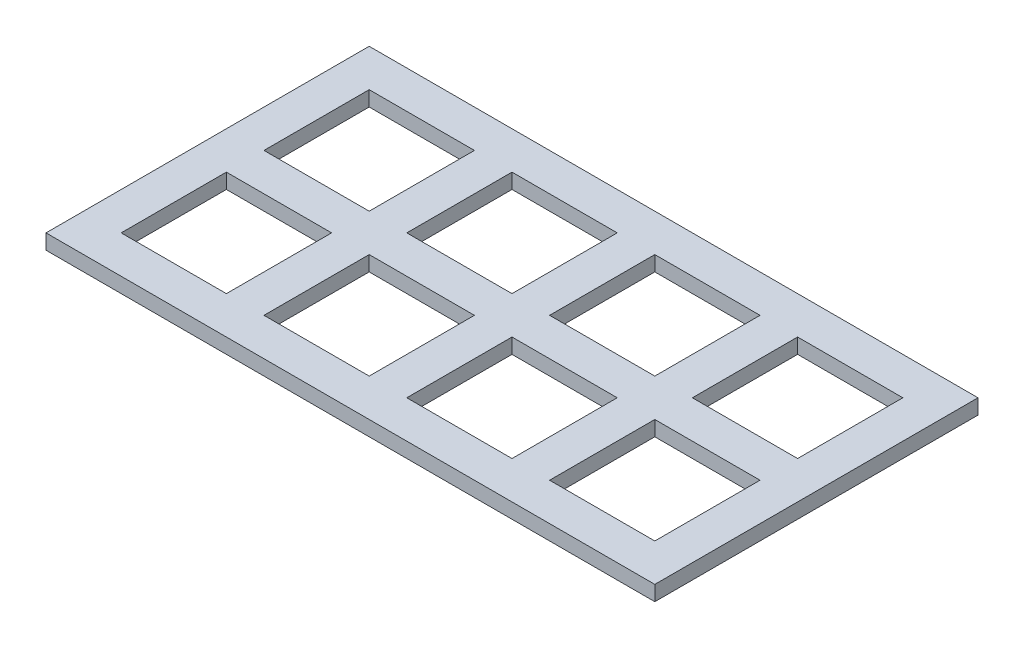
SolidWorks part; units mm, degrees
ref_plane "Front Plane" through (0, 0, 0) normal (0, 0, 1) x (1, 0, 0)
ref_plane "Top Plane" through (0, 0, 0) normal (0, 1, 0) x (1, 0, 0)
ref_plane "Right Plane" through (0, 0, 0) normal (1, 0, 0) x (0, 0, -1)
sketch "Sketch1" plane through (0, 0, 0) normal (0, 1, 0) x (1, 0, 0)
  line L0 (-195.16, 0) -> (180.7199, 0) construction
  line L1 (0, 112.1295) -> (0, -97.9082) construction
  line L2 (21.5, 2.5) -> (21.5, 16.5)
  line L3 (2.5, 2.5) -> (16.5, 2.5)
  line L4 (2.5, 2.5) -> (2.5, 16.5)
  line L5 (2.5, 16.5) -> (16.5, 16.5)
  line L6 (16.5, 2.5) -> (16.5, 16.5)
  line L7 (21.5, 2.5) -> (35.5, 2.5)
  line L8 (35.5, 2.5) -> (35.5, 16.5)
  line L9 (21.5, 16.5) -> (35.5, 16.5)
  line L10 (-40.5, 21.5) -> (40.5, 21.5)
  line L13 (40.5, 16.5) -> (40.5, 0)
  line L14 (-40.5, 16.5) -> (-40.5, -16.5)
  line L17 (-21.5, 16.5) -> (-35.5, 16.5)
  line L18 (-35.5, 2.5) -> (-35.5, 16.5)
  line L19 (-21.5, 2.5) -> (-35.5, 2.5)
  line L20 (-16.5, 2.5) -> (-16.5, 16.5)
  line L21 (-2.5, 16.5) -> (-16.5, 16.5)
  line L22 (-2.5, 2.5) -> (-2.5, 16.5)
  line L23 (-2.5, 2.5) -> (-16.5, 2.5)
  line L24 (-21.5, 2.5) -> (-21.5, 16.5)
  line L25 (40.5, -16.5) -> (40.5, 0)
  line L26 (-21.5, -2.5) -> (-21.5, -16.5)
  line L27 (-2.5, -2.5) -> (-16.5, -2.5)
  line L28 (-2.5, -2.5) -> (-2.5, -16.5)
  line L29 (-2.5, -16.5) -> (-16.5, -16.5)
  line L30 (-16.5, -2.5) -> (-16.5, -16.5)
  line L31 (-21.5, -2.5) -> (-35.5, -2.5)
  line L32 (-35.5, -2.5) -> (-35.5, -16.5)
  line L33 (-21.5, -16.5) -> (-35.5, -16.5)
  line L38 (-40.5, -21.5) -> (40.5, -21.5)
  line L39 (21.5, -16.5) -> (35.5, -16.5)
  line L40 (35.5, -2.5) -> (35.5, -16.5)
  line L41 (21.5, -2.5) -> (35.5, -2.5)
  line L42 (16.5, -2.5) -> (16.5, -16.5)
  line L43 (2.5, -16.5) -> (16.5, -16.5)
  line L44 (2.5, -2.5) -> (2.5, -16.5)
  line L45 (2.5, -2.5) -> (16.5, -2.5)
  line L46 (21.5, -2.5) -> (21.5, -16.5)
  line L47 (40.5, -16.5) -> (40.5, -21.5)
  line L48 (40.5, 16.5) -> (40.5, 21.5)
  line L49 (-40.5, 16.5) -> (-40.5, 21.5)
  line L50 (-40.5, -16.5) -> (-40.5, -21.5)
  point P28 (0, 21.5)
  point P36 (40.5, 8.25)
  point P37 (40.5, -8.25)
  point P40 (-40.5, 0)
  point P60 (0, -21.5)
  dimension "D3" = 81
  dimension "D4" = 43
  dimension "D6" = 14
  dimension "D7" = 5
  dimension "D1" = 2
extrude "Boss-Extrude1" add sketch "Sketch1" along normal blind 2
